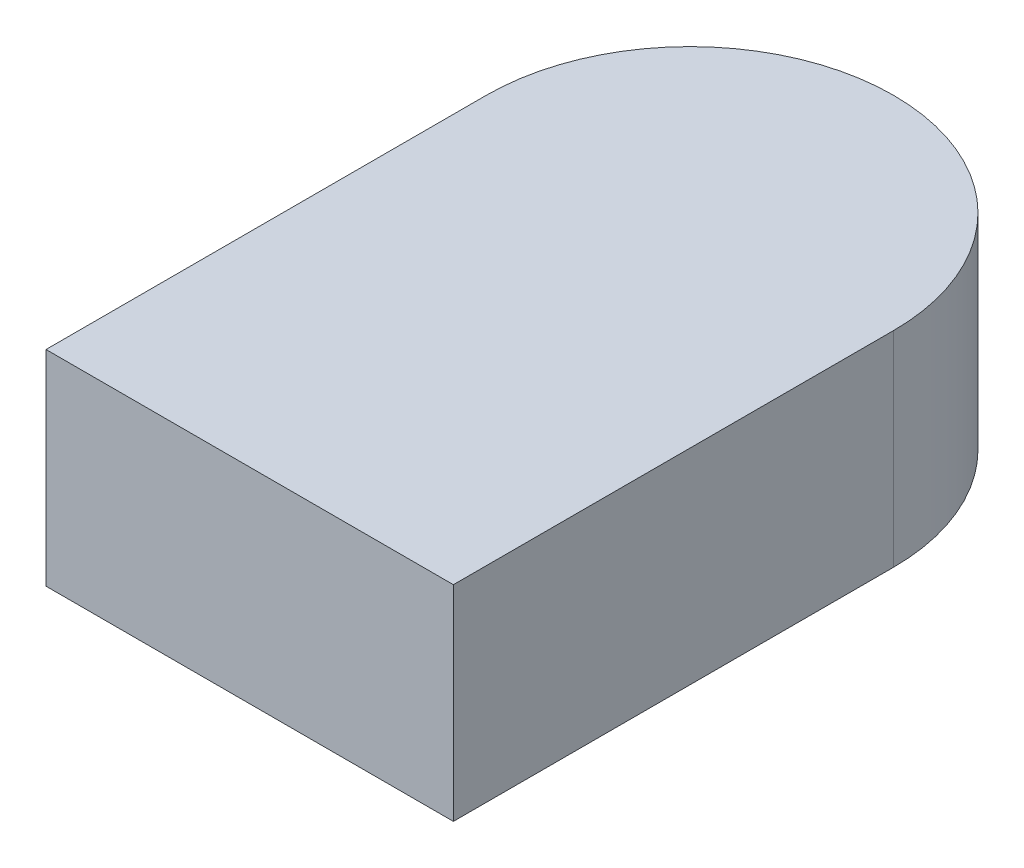
SolidWorks part; units mm, degrees
ref_plane "Front Plane" through (0, 0, 0) normal (0, 0, 1) x (1, 0, 0)
ref_plane "Top Plane" through (0, 0, 0) normal (0, 1, 0) x (1, 0, 0)
ref_plane "Right Plane" through (0, 0, 0) normal (1, 0, 0) x (0, 0, -1)
sketch "Sketch1" plane through (0, 0, 0) normal (0, 1, 0) x (1, 0, 0)
  line L0 (-15.5, 0) -> (-15.5, -33.5)
  line L1 (-15.5, -33.5) -> (15.5, -33.5)
  line L2 (15.5, -33.5) -> (15.5, 0)
  arc A0 (-15.5, 0) -> (15.5, 0) centre (0, 0) cw
  point P4 (0, 15.5)
  point P7 (0, 0)
  dimension "D1" = 31
  dimension "D2" = 49
extrude "Boss-Extrude1" add sketch "Sketch1" along normal blind 15.6
